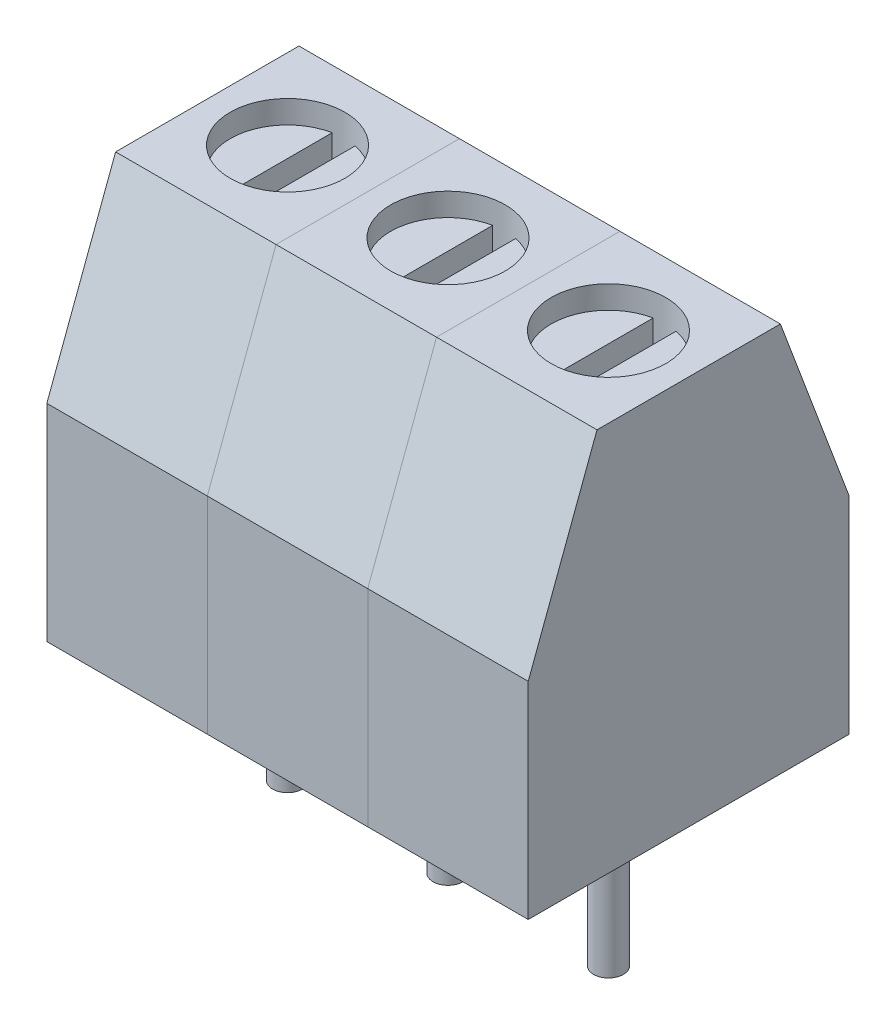
SolidWorks part; units mm, degrees
ref_plane "정면" through (0, 0, 0) normal (0, 0, 1) x (1, 0, 0)
ref_plane "윗면" through (0, 0, 0) normal (0, 1, 0) x (1, 0, 0)
ref_plane "우측면" through (0, 0, 0) normal (1, 0, 0) x (0, 0, -1)
sketch "스케치1" plane through (0, 0, 0) normal (1, 0, 0) x (0, 0, -1)
  line L0 (0, 4.5) -> (0, 8.5) construction
  line L1 (0, 0) -> (7, 0)
  line L2 (0, 0) -> (0, 4.5)
  line L3 (0, 8.5) -> (7, 8.5) construction
  line L4 (7, 0) -> (7, 4.5)
  line L5 (1.5, 8.5) -> (5.5, 8.5)
  line L6 (1.5, 8.5) -> (0, 4.5)
  line L7 (5.5, 8.5) -> (7, 4.5)
  line L8 (7, 4.5) -> (7, 8.5) construction
  line L9 (0, 4.5) -> (7, 4.5) construction
  point P10 (3.5, 8.5)
  dimension "D1" = 4
  dimension "D2" = 7
  dimension "D3" = 8.5
  dimension "D4" = 4.5
extrude "보스-돌출1" add sketch "스케치1" along normal blind 3.5
sketch "스케치3" plane through (0, 0, -7) normal (0, 0, -1) x (-1, 0, 0)
  line L0 (-3.5, 4.5) -> (0, 4.5) construction
  line L1 (-3.25, 0.5) -> (-0.25, 0.5)
  line L2 (-3.25, 0.5) -> (-3.25, 4.5)
  line L3 (-3.25, 4.5) -> (-0.25, 4.5)
  line L4 (-0.25, 0.5) -> (-0.25, 4.5)
  line L5 (-3.5, 0) -> (-3.5, 4.5) construction
  line L6 (0, 0) -> (0, 4.5) construction
  line L7 (-3.5, 0) -> (0, 0) construction
  dimension "D1" = 0.25
  dimension "D2" = 0.25
  dimension "D3" = 0.5
extrude "컷-돌출1" cut sketch "스케치3" against normal blind 1.5
sketch "스케치4" plane through (0, 8.5, 0) normal (0, 1, 0) x (1, 0, 0)
  circle A0 centre (1.75, 3.5) radius 1.25
extrude "컷-돌출2" cut sketch "스케치4" against normal blind 0.5
sketch "스케치5" plane through (0, 8, 0) normal (0, 1, 0) x (1, 0, 0)
  line L2 (1.5001, 4.7248) -> (1.5001, 2.2752)
  line L4 (1.9999, 4.7248) -> (1.9999, 2.2752)
  line L5 (1.5001, 4.7248) -> (1.9999, 2.2752) construction
  line L6 (1.5001, 2.2752) -> (1.9999, 4.7248) construction
  arc A0 (1.5001, 2.2752) -> (1.9999, 2.2752) centre (1.75, 3.5) ccw
  circle A1 centre (1.75, 3.5) radius 1.25
  arc A2 (1.9999, 4.7248) -> (1.5001, 4.7248) centre (1.75, 3.5) ccw
  dimension "D1" = 0
extrude "컷-돌출3" cut sketch "스케치5" against normal blind 0.5
sketch "스케치7" plane through (0, 0, -5.5) normal (0, 0, -1) x (-1, 0, 0)
  line L0 (-3.25, 4.5) -> (-3.25, 0.5) construction
  line L1 (-3.25, 0.5) -> (-0.25, 0.5) construction
  circle A0 centre (-1.75, 2) radius 1
  dimension "D1" = 1.5
  dimension "D2" = 2
  dimension "D3" = 1.5
extrude "컷-돌출4" cut sketch "스케치7" against normal blind 3
pattern_linear "선형 패턴1" [suppressed] count 3 spacing 3.5
sketch "Sketch1" plane through (0, 0, 0) normal (0, -1, 0) x (1, 0, 0)
  line L4 (0, 0) -> (0, -7)
  line L5 (0, -7) -> (3.5, -7)
  line L6 (3.5, -7) -> (3.5, 0)
  line L7 (3.5, 0) -> (0, 0)
  line L8 (0, 0) -> (0, -7)
  line L9 (0, -7) -> (3.5, -7)
  line L10 (3.5, -7) -> (3.5, 0)
  line L11 (3.5, 0) -> (0, 0)
  circle A0 centre (1.75, -3.5) radius 0.325
  point P6 (0, 0)
  point P7 (0, 0)
  dimension "D2" = 1.75
  dimension "D3" = 3.5
  dimension "D4" = 7
  dimension "D5" = 3.5
  dimension "D1" = 0
extrude "Boss-Extrude1" add sketch "Sketch1" along normal blind 3.5 contours A0
pattern_linear "LPattern1" count 3 spacing 3.5 along (1, 0, 0) of bodies 108
